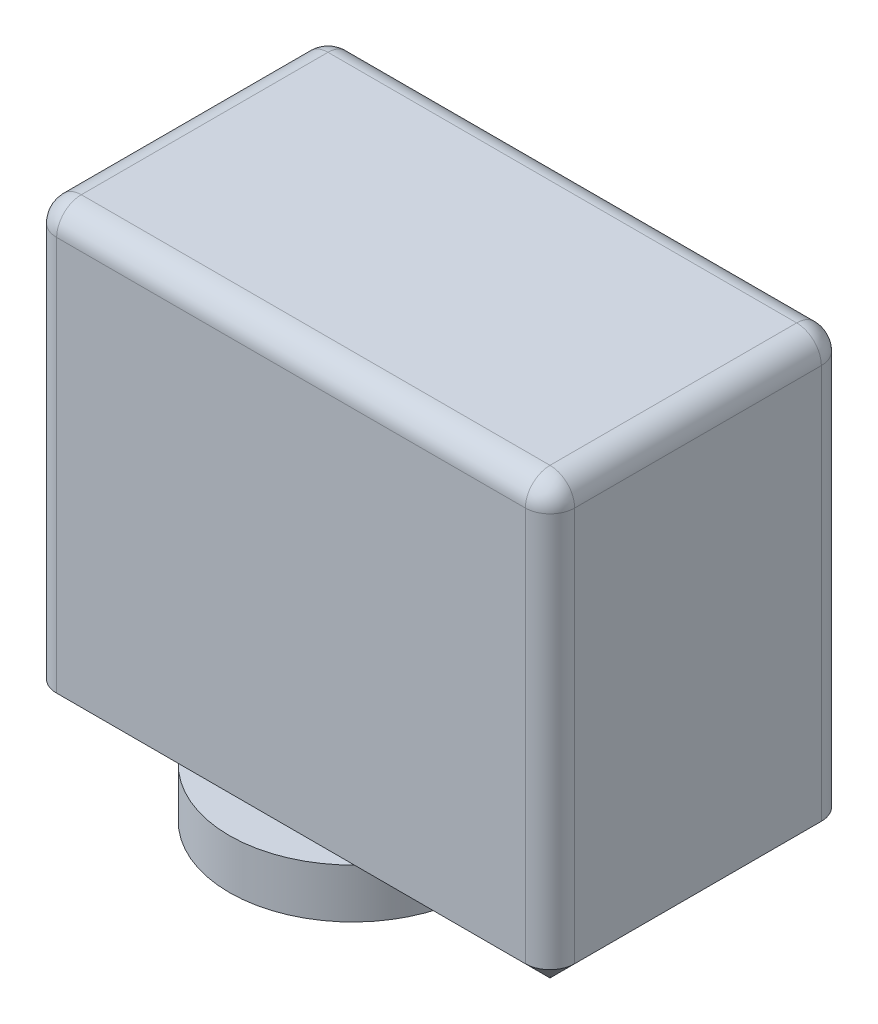
SolidWorks part; units mm, degrees
ref_plane "Front Plane" through (0, 0, 0) normal (0, 0, 1) x (1, 0, 0)
ref_plane "Top Plane" through (0, 0, 0) normal (0, 1, 0) x (1, 0, 0)
ref_plane "Right Plane" through (0, 0, 0) normal (1, 0, 0) x (0, 0, -1)
sketch "草图1" plane through (0, 0, 0) normal (0, 1, 0) x (1, 0, 0)
  circle A0 centre (0, 0) radius 5
extrude "凸台-拉伸1" add sketch "草图1" along normal blind 2
sketch "草图2" plane through (0, 2, 0) normal (0, 1, 0) x (1, 0, 0)
  circle A0 centre (0, 0) radius 2
extrude "凸台-拉伸2" add sketch "草图2" along normal blind 1.5
sketch "草图3" plane through (0, 3.5, 0) normal (0, 1, 0) x (1, 0, 0)
  line L1 (0, -6) -> (-7, -6)
  line L2 (0, -6) -> (14, -6)
  line L4 (0, 6) -> (-7, 6)
  line L5 (0, 6) -> (14, 6)
  line L6 (-7, 6) -> (-7, -6)
  line L7 (14, -6) -> (14, 6)
extrude "凸台-拉伸3" add sketch "草图3" along normal blind 18
fillet "圆角1" radius 1 8 edges at (-7, 21.5, 0) (3.5, 21.5, -6) (14, 21.5, 0) (3.5, 21.5, 6) (14, 12.5, 6) (14, 12.5, -6) (-7, 12.5, 6) (-7, 12.5, -6)
chamfer "倒角1" distance 1 angle 45 8 edges at (3.5, 3.5, 6) (13.7071, 3.5, 5.7071) (-6.7071, 3.5, 5.7071) (14, 3.5, 0) (-7, 3.5, 0) (13.7071, 3.5, -5.7071) (-6.7071, 3.5, -5.7071) (3.5, 3.5, -6)
scale "缩放比例1" scale about centroid uniform scaling yes scale factor 1.703704
